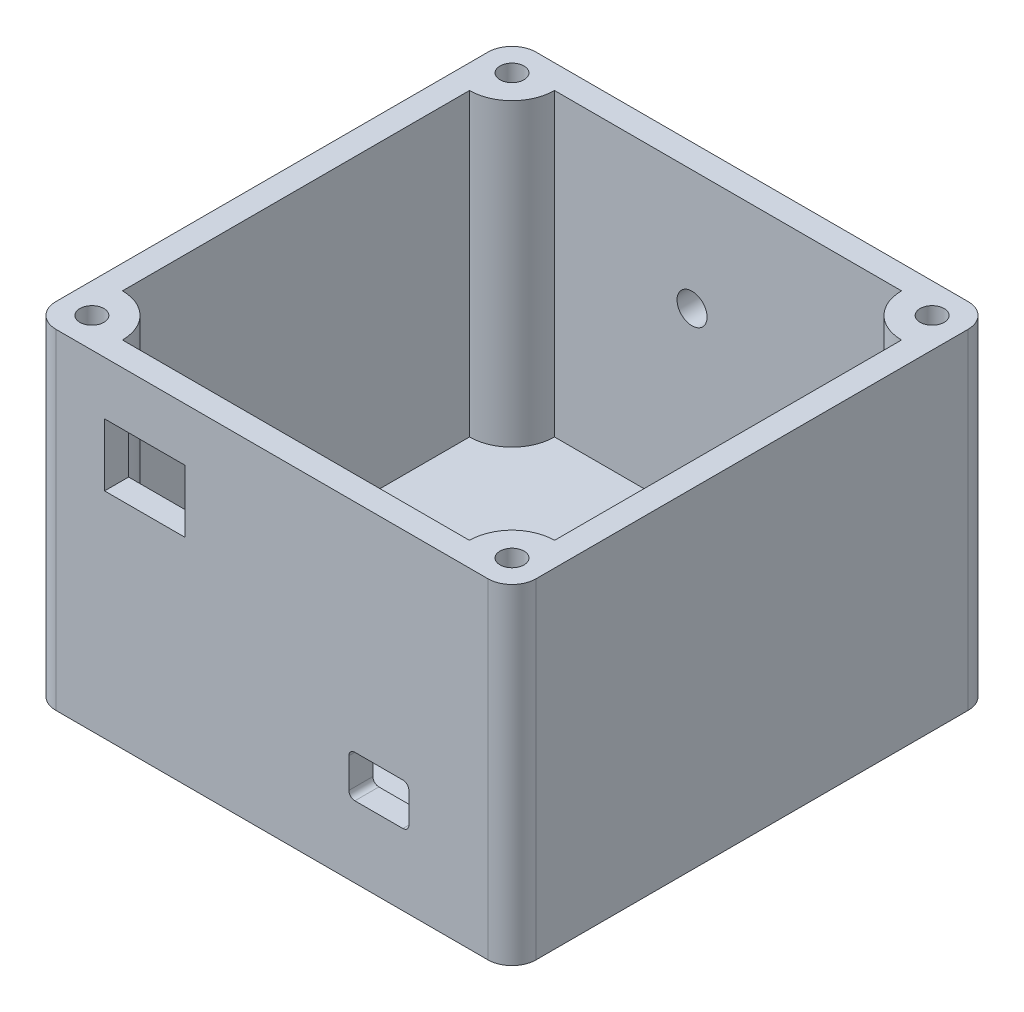
SolidWorks part; units mm, degrees
ref_plane "Front Plane" through (0, 0, 0) normal (0, 0, 1) x (1, 0, 0)
ref_plane "Top Plane" through (0, 0, 0) normal (0, 1, 0) x (1, 0, 0)
ref_plane "Right Plane" through (0, 0, 0) normal (1, 0, 0) x (0, 0, -1)
sketch "Sketch1" plane through (0, 0, 0) normal (0, 1, 0) x (1, 0, 0)
  line L5 (-87.5188, 5.08) -> (-14.0812, 5.08)
  line L6 (-96.52, 14.0812) -> (-96.52, 87.5188)
  line L7 (-87.5188, 96.52) -> (-14.0812, 96.52)
  line L8 (-5.08, 14.0812) -> (-5.08, 87.5188)
  line L9 (-96.52, 5.08) -> (-5.08, 96.52) construction
  line L10 (-96.52, 96.52) -> (-5.08, 5.08) construction
  arc A0 (-96.52, 14.0812) -> (-87.5188, 5.08) centre (-96.52, 5.08) cw
  arc A1 (-96.52, 87.5188) -> (-87.5188, 96.52) centre (-96.52, 96.52) ccw
  arc A2 (-5.08, 14.0812) -> (-14.0812, 5.08) centre (-5.08, 5.08) ccw
  arc A3 (-5.08, 87.5188) -> (-14.0812, 96.52) centre (-5.08, 96.52) cw
  point P2 (0, 0)
  point P5 (-50.8, 50.8)
  dimension "D3" = 91.44
  dimension "D4" = 91.44
sketch "Sketch3" plane through (0, 0, 0) normal (0, 1, 0) x (1, 0, 0)
  line L0 (-96.52, 14.0812) -> (-96.52, 87.5188) construction
  line L1 (-96.52, 0) -> (-5.08, 0)
  line L2 (-101.6, 5.08) -> (-101.6, 96.52)
  line L3 (-96.52, 101.6) -> (-5.08, 101.6)
  line L4 (0, 5.08) -> (0, 96.52)
  line L5 (-101.6, 0) -> (0, 101.6) construction
  line L6 (-101.6, 101.6) -> (0, 0) construction
  arc A0 (-5.08, 0) -> (0, 5.08) centre (-5.08, 5.08) ccw
  arc A1 (0, 96.52) -> (-5.08, 101.6) centre (-5.08, 96.52) ccw
  arc A2 (-96.52, 101.6) -> (-101.6, 96.52) centre (-96.52, 96.52) ccw
  arc A3 (-96.52, 0) -> (-101.6, 5.08) centre (-96.52, 5.08) cw
  point P0 (-50.8, 50.8)
  dimension "D3" = 5.08
  dimension "D1" = 101.6
  dimension "D2" = 5.08
sketch "Sketch4" plane through (0, 0, 0) normal (0, 1, 0) x (1, 0, 0)
  line L0 (-101.6, 0) -> (0, 101.6) construction
  line L1 (-96.52, 0) -> (-5.08, 0) construction
  circle A0 centre (-95.25, 6.35) radius 2.54
  circle A4 centre (-6.35, 6.35) radius 2.54
  circle A5 centre (-6.35, 95.25) radius 2.54
  circle A6 centre (-95.25, 95.25) radius 2.54
  dimension "D1" = 6.35
extrude "Boss-Extrude1" add sketch "Sketch3" along normal blind 69.85
extrude "Cut-Extrude1" cut sketch "Sketch1" against normal blind 63.5 from surface at 69.85 starting at face at (-50.8, 69.85, -50.8)
extrude "Cut-Extrude2" cut sketch "Sketch4" against normal blind 5.08 from surface at 69.85 starting at face at (-50.8, 69.85, -50.8)
sketch "Sketch5" plane through (0, 0, 0) normal (0, 0, 1) x (1, 0, 0)
  line L1 (-86.2102, 58.5929) -> (-69.1922, 58.5929)
  line L2 (-86.2102, 58.5929) -> (-86.2102, 45.3849)
  line L3 (-86.2102, 45.3849) -> (-69.1922, 45.3849)
  line L4 (-69.1922, 58.5929) -> (-69.1922, 45.3849)
  dimension "D1" = 13.208
  dimension "D2" = 17.018
extrude "Cut-Extrude3" cut sketch "Sketch5" against normal blind 12.7
sketch "Sketch6" plane through (0, 0, 0) normal (0, 0, 1) x (1, 0, 0)
  line L1 (-33.2528, 23.9643) -> (-23.0928, 23.9643)
  line L2 (-34.5228, 22.6943) -> (-34.5228, 16.3443)
  line L3 (-33.2528, 15.0743) -> (-23.0928, 15.0743)
  line L4 (-21.8228, 22.6943) -> (-21.8228, 16.3443)
  arc A0 (-34.5228, 22.6943) -> (-33.2528, 23.9643) centre (-33.2528, 22.6943) cw
  arc A1 (-34.5228, 16.3443) -> (-33.2528, 15.0743) centre (-33.2528, 16.3443) ccw
  arc A2 (-23.0928, 15.0743) -> (-21.8228, 16.3443) centre (-23.0928, 16.3443) ccw
  arc A3 (-21.8228, 22.6943) -> (-23.0928, 23.9643) centre (-23.0928, 22.6943) ccw
  point P6 (-34.5228, 23.9643)
  point P11 (-21.8228, 15.0743)
  point P14 (-21.8228, 23.9643)
  dimension "D3" = 1.27
  dimension "D4" = 1.27
  dimension "D1" = 12.7
  dimension "D2" = 8.89
extrude "Cut-Extrude4" cut sketch "Sketch6" against normal blind 12.7
sketch "Sketch7" plane through (0, 0, -101.6) normal (0, 0, -1) x (-1, 0, 0)
  line L0 (5.08, 69.85) -> (96.52, 69.85) construction
  line L1 (96.52, 69.85) -> (96.52, 0) construction
  circle A0 centre (58.42, 44.45) radius 3.175
  dimension "D1" = 25.4
  dimension "D2" = 38.1
extrude "Cut-Extrude5" cut sketch "Sketch7" against normal blind 7.62
sketch "Sketch9" plane through (-101.6, 0, 0) normal (-1, 0, 0) x (0, 0, 1)
  text T0 "SitkaNet Hub\r\nUSB Power\r\nVersion 3\r\n"
extrude "Cut-Extrude6" cut sketch "Sketch9" against normal blind 2.54
